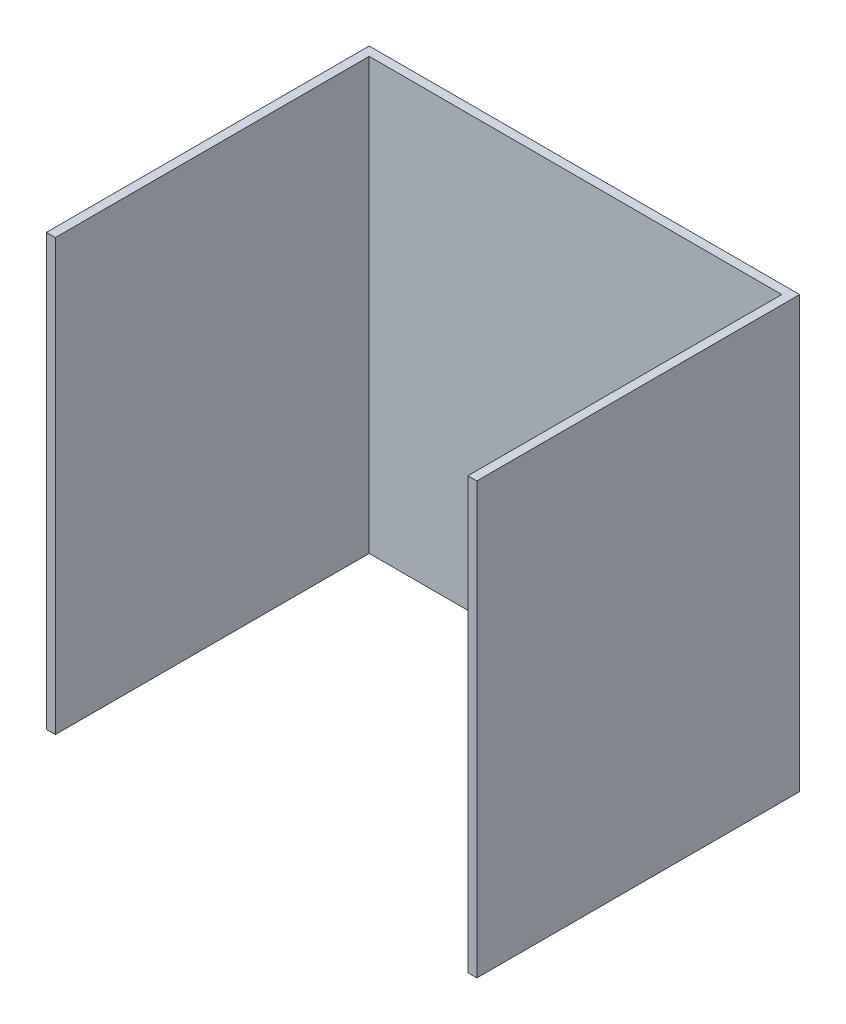
SolidWorks part; units mm, degrees
ref_plane "Front Plane" through (0, 0, 0) normal (0, 0, 1) x (1, 0, 0)
ref_plane "Top Plane" through (0, 0, 0) normal (0, 1, 0) x (1, 0, 0)
ref_plane "Right Plane" through (0, 0, 0) normal (1, 0, 0) x (0, 0, -1)
sketch "Sketch1" plane through (0, 0, 0) normal (0, 1, 0) x (1, 0, 0)
  line L1 (0, 0) -> (609.6, 0)
  line L2 (0, 0) -> (0, 457.2)
  line L3 (0, 457.2) -> (609.6, 457.2)
  line L4 (609.6, 0) -> (609.6, 457.2)
  dimension "D1" = 609.6
  dimension "D2" = 457.2
extrude "Boss-Extrude1" add sketch "Sketch1" along normal blind 609.6
shell "Shell1" thickness 12.7
